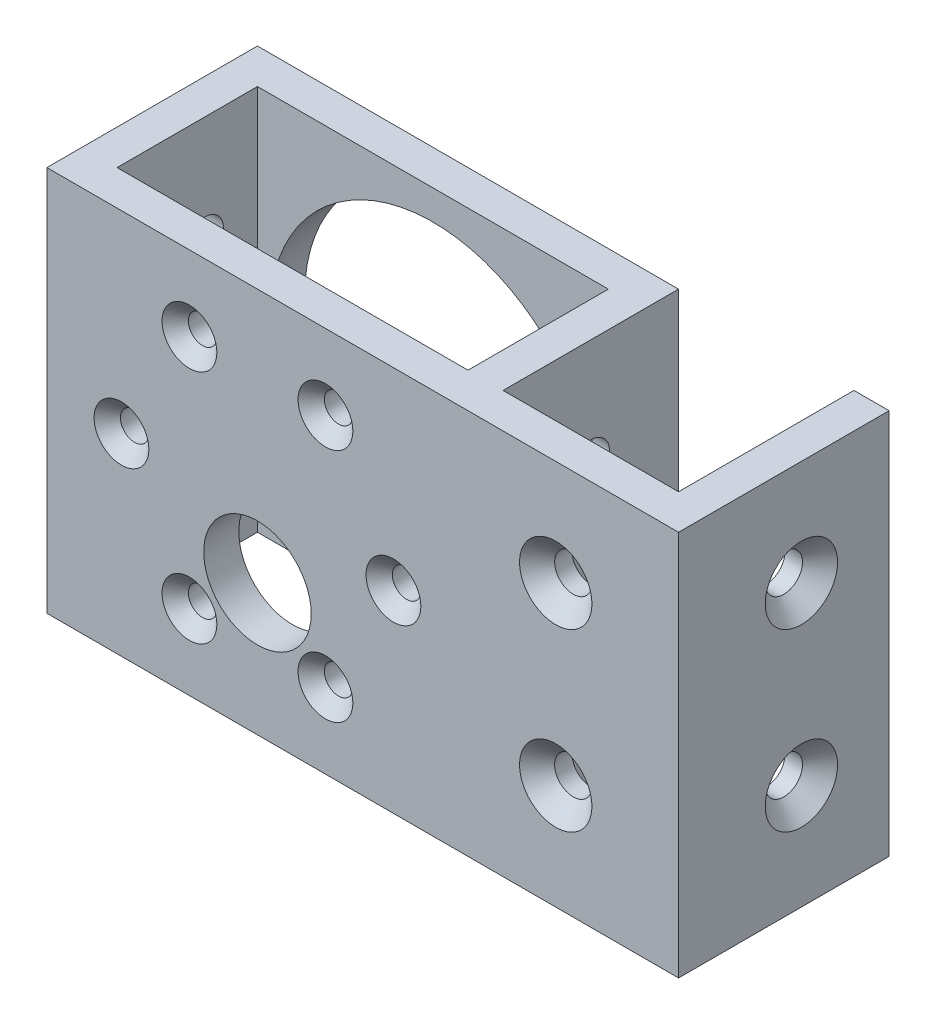
SolidWorks part; units mm, degrees
ref_plane "Front Plane" through (0, 0, 0) normal (0, 0, 1) x (1, 0, 0)
ref_plane "Top Plane" through (0, 0, 0) normal (0, 1, 0) x (1, 0, 0)
ref_plane "Right Plane" through (0, 0, 0) normal (1, 0, 0) x (0, 0, -1)
sketch "Sketch1" plane through (0, 0, 0) normal (0, 1, 0) x (1, 0, 0)
  line L0 (0, 20) -> (0, 0)
  line L1 (0, 0) -> (-20, 0)
  line L2 (-20, 0) -> (-20, 20)
  line L3 (0, 20) -> (4, 20)
  line L4 (4, 20) -> (4, -4)
  line L5 (4, -4) -> (-24, -4)
  line L6 (-24, 0) -> (-24, 16)
  line L7 (-24, 20) -> (-20, 20)
  line L8 (-24, -4) -> (-68, -4)
  line L9 (-68, -4) -> (-68, 0)
  line L10 (-64, 0) -> (-24, 0)
  line L11 (-24, 0) -> (-24, 20)
  line L12 (-68, 20) -> (-68, 16)
  line L13 (-64, 16) -> (-24, 16)
  line L14 (-24, 16) -> (-24, 20)
  line L15 (-68, 20) -> (-24, 20)
  line L16 (-68, 0) -> (-68, 16)
  line L17 (-64, 16) -> (-64, 0)
  dimension "D1" = 20
  dimension "D2" = 20
  dimension "D3" = 20
  dimension "D4" = 4
  dimension "D5" = 4
  dimension "D6" = 4
  dimension "D7" = 4
  dimension "D8" = 44
  dimension "D9" = 4
extrude "Boss-Extrude1" add sketch "Sketch1" along normal blind 44
sketch "Sketch2" plane through (0, 0, -20) normal (0, 0, -1) x (-1, 0, 0)
  line L0 (68, 44) -> (20, 44) construction
  line L1 (68, 44) -> (68, 0) construction
  circle A0 centre (44, 22) radius 18.625
  dimension "D1" = 37.25
  dimension "D2" = 22
  dimension "D3" = 24
extrude "Cut-Extrude1" cut sketch "Sketch2" against normal up to next
sketch "Sketch3" plane through (0, 0, 4) normal (0, 0, 1) x (1, 0, 0)
  line L0 (-68, 44) -> (-68, 0) construction
  line L1 (-28.5, 22) -> (-36.25, 35.4234)
  line L2 (-36.25, 35.4234) -> (-51.75, 35.4234)
  line L3 (-51.75, 35.4234) -> (-59.5, 22)
  line L4 (-59.5, 22) -> (-51.75, 8.5766)
  line L5 (-51.75, 8.5766) -> (-36.25, 8.5766)
  line L6 (-36.25, 8.5766) -> (-28.5, 22)
  line L7 (4, 0) -> (-68, 0) construction
  circle A0 centre (-44, 22) radius 13.4234 construction
  circle A1 centre (-51.75, 35.4234) radius 1.625
  circle A2 centre (-36.25, 35.4234) radius 1.625
  circle A3 centre (-28.5, 22) radius 1.625
  circle A4 centre (-36.25, 8.5766) radius 1.625
  circle A5 centre (-51.75, 8.5766) radius 1.625
  circle A6 centre (-59.5, 22) radius 1.625
  circle A7 centre (-44, 15) radius 6.125
  dimension "D4" = 3.25
  dimension "D5" = 3.25
  dimension "D6" = 3.25
  dimension "D7" = 3.25
  dimension "D8" = 3.25
  dimension "D9" = 3.25
  dimension "D11" = 12.25
  dimension "D1" = 15.5
  dimension "D2" = 24
  dimension "D3" = 22
  dimension "D10" = 7
extrude "Cut-Extrude2" cut sketch "Sketch3" against normal up to next contours A7 | A1 | A2 | A3 | A4 | A5 | A6
sketch "Sketch4" plane through (4, 0, 0) normal (1, 0, 0) x (0, 0, -1)
  line L0 (20, 0) -> (-4, 0) construction
  line L1 (20, 44) -> (-4, 44) construction
  line L2 (-4, 44) -> (-4, 0) construction
  circle A0 centre (10, 32) radius 2.125
  circle A1 centre (10, 12) radius 2.125
  dimension "D1" = 4.25
  dimension "D2" = 4.25
  dimension "D6" = 14
  dimension "D3" = 12
  dimension "D4" = 12
  dimension "D5" = 14
extrude "Cut-Extrude3" cut sketch "Sketch4" against normal through all
sketch "Sketch5" plane through (0, 0, 4) normal (0, 0, 1) x (1, 0, 0)
  line L0 (4, 44) -> (-68, 44) construction
  line L1 (4, 0) -> (-68, 0) construction
  line L2 (4, 44) -> (4, 0) construction
  circle A0 centre (-10, 32) radius 2.125
  circle A1 centre (-10, 12) radius 2.125
  dimension "D1" = 4.25
  dimension "D2" = 4.25
  dimension "D3" = 12
  dimension "D4" = 12
  dimension "D5" = 14
  dimension "D6" = 14
extrude "Cut-Extrude4" cut sketch "Sketch5" against normal through all
chamfer "Chamfer1" distance 2 6 edges at (4, 32, -12.125) (-24, 12, -7.875) (-24, 32, -7.875) (-7.875, 32, 4) (-7.875, 12, 4) (4, 12, -12.125)
chamfer "Chamfer2" distance 1.5 6 edges at (-57.875, 22, 4) (-50.125, 8.5766, 4) (-34.625, 8.5766, 4) (-26.875, 22, 4) (-34.625, 35.4234, 4) (-50.125, 35.4234, 4)
